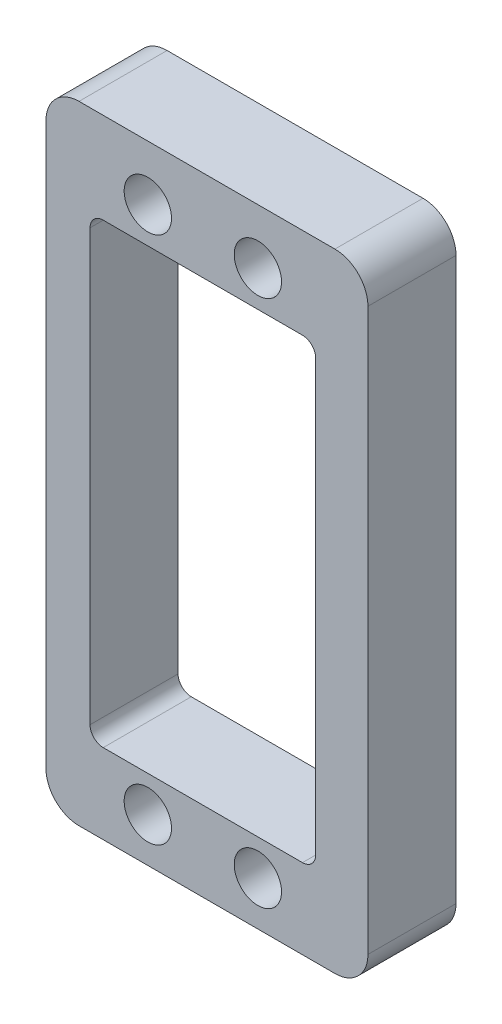
SolidWorks part; units mm, degrees
material "玻纤"
ref_plane "前视基准面" through (0, 0, 0) normal (0, 0, 1) x (1, 0, 0)
ref_plane "上视基准面" through (0, 0, 0) normal (0, 1, 0) x (1, 0, 0)
ref_plane "右视基准面" through (0, 0, 0) normal (1, 0, 0) x (0, 0, -1)
sketch "草图1" plane through (0, 0, 0) normal (0, 0, 1) x (1, 0, 0)
  line L1 (0, 0) -> (100, 0)
  line L2 (0, 0) -> (0, -100)
  line L3 (0, -100) -> (100, -100)
  line L4 (100, 0) -> (100, -100)
  dimension "D1" = 100
  dimension "D2" = 100
extrude "凸台-拉伸1" add sketch "草图1" along normal blind 8
sketch "草图2" plane through (0, 0, 8) normal (0, 0, 1) x (1, 0, 0)
  line L4 (0, 0) -> (0, -100)
  line L5 (0, -100) -> (100, -100)
  line L6 (100, -100) -> (100, 0)
  line L7 (100, 0) -> (0, 0)
  line L8 (0, 0) -> (0, -100)
  line L9 (0, -100) -> (100, -100)
  line L10 (100, -100) -> (100, 0)
  line L11 (100, 0) -> (0, 0)
  circle A0 centre (80, -53) radius 2.15
  circle A1 centre (90, -53) radius 2.15
  circle A2 centre (90, -5) radius 2.15
  circle A3 centre (80, -5) radius 2.15
  dimension "D2" = 4.3
  dimension "D5" = 10
  dimension "D6" = 48
  dimension "D7" = 5
  dimension "D8" = 10
  dimension "D1" = 0
  dimension "D3" = 2
  dimension "D4" = 2
extrude "切除-拉伸1" cut sketch "草图2" against normal through all contours A3 | A2 | A0 | A1
sketch "草图3" plane through (0, 0, 8) normal (0, 0, 1) x (1, 0, 0)
  line L4 (0, 0) -> (0, -100)
  line L5 (0, -100) -> (100, -100)
  line L6 (100, -100) -> (100, 0)
  line L7 (100, 0) -> (0, 0)
  line L8 (0, 0) -> (0, -100)
  line L9 (0, -100) -> (100, -100)
  line L10 (100, -100) -> (100, 0)
  line L11 (100, 0) -> (0, 0)
  circle A0 centre (73, -95) radius 2.15
  circle A1 centre (73, -85) radius 2.15
  circle A2 centre (85, -85) radius 2.15
  circle A3 centre (85, -95) radius 2.15
  dimension "D2" = 4.3
  dimension "D5" = 10
  dimension "D6" = 12
  dimension "D7" = 5
  dimension "D8" = 15
  dimension "D1" = 0
  dimension "D3" = 2
  dimension "D4" = 2
extrude "切除-拉伸2" cut sketch "草图3" against normal through all contours A1 | A2 | A3 | A0
sketch "草图4" plane through (0, 0, 8) normal (0, 0, 1) x (1, 0, 0)
  line L4 (0, 0) -> (0, -100)
  line L5 (0, -100) -> (100, -100)
  line L6 (100, -100) -> (100, 0)
  line L7 (100, 0) -> (0, 0)
  line L8 (0, 0) -> (0, -100)
  line L9 (0, -100) -> (100, -100)
  line L10 (100, -100) -> (100, 0)
  line L11 (100, 0) -> (0, 0)
  circle A0 centre (71.5, -100) radius 9.5
  circle M5 centre (73, -95) radius 2.15
  dimension "D2" = 19
  dimension "D3" = 28.5
  dimension "D1" = 0
extrude "切除-拉伸3" cut sketch "草图4" against normal through all contours L9 A0 M5
sketch "草图5" plane through (0, 0, 8) normal (0, 0, 1) x (1, 0, 0)
  line L0 (85, -1.0404) -> (85, -63.0979) construction
  line L1 (65.9696, -29) -> (93.5663, -29) construction
  line L3 (74.75, -8.25) -> (95.25, -8.25)
  line L4 (74.75, -8.25) -> (74.75, -49.75)
  line L5 (81, -100) -> (100, -100)
  line L6 (100, -100) -> (100, 0)
  line L7 (100, 0) -> (0, 0)
  line L8 (0, 0) -> (0, -100)
  line L9 (0, -100) -> (62, -100)
  line L10 (81, -100) -> (100, -100)
  line L11 (100, -100) -> (100, 0)
  line L12 (100, 0) -> (0, 0)
  line L13 (0, 0) -> (0, -100)
  line L14 (0, -100) -> (62, -100)
  line L15 (74.75, -49.75) -> (95.25, -49.75)
  line L16 (95.25, -8.25) -> (95.25, -49.75)
  circle A0 centre (80, -5) radius 2.15 construction
  arc A1 (81, -100) -> (62, -100) centre (71.5, -100) ccw
  arc A2 (81, -100) -> (62, -100) centre (71.5, -100) ccw
  circle A3 centre (80, -5) radius 2.15
  circle A4 centre (90, -5) radius 2.15 construction
  circle A5 centre (90, -5) radius 2.15
  circle A6 centre (80, -53) radius 2.15 construction
  circle A7 centre (80, -53) radius 2.15
  circle A8 centre (90, -53) radius 2.15 construction
  circle A9 centre (90, -53) radius 2.15
  dimension "D2" = 41.5
  dimension "D3" = 20.5
  dimension "D1" = 0
extrude "切除-拉伸4" cut sketch "草图5" against normal blind 10 contours L4 L3 L16 L15
sketch "草图6" plane through (0, 0, 8) normal (0, 0, 1) x (1, 0, 0)
  line L0 (55, 0) -> (55, -100)
  line L5 (81, -100) -> (100, -100)
  line L6 (100, -100) -> (100, 0)
  line L7 (100, 0) -> (0, 0)
  line L8 (0, 0) -> (0, -100)
  line L9 (0, -100) -> (62, -100)
  line L10 (81, -100) -> (100, -100)
  line L11 (100, -100) -> (100, 0)
  line L12 (100, 0) -> (0, 0)
  line L13 (0, 0) -> (0, -100)
  line L14 (0, -100) -> (62, -100)
  circle A0 centre (73, -85) radius 2.15 construction
  arc A1 (81, -100) -> (62, -100) centre (71.5, -100) ccw
  arc A2 (81, -100) -> (62, -100) centre (71.5, -100) ccw
  circle A3 centre (73, -85) radius 2.15
  dimension "D2" = 45
  dimension "D1" = 0
extrude "切除-拉伸5" cut sketch "草图6" against normal blind 10
fillet "圆角2" radius 1.2 4 edges at (74.75, -8.25, 4) (95.25, -49.75, 4) (74.75, -49.75, 4) (95.25, -8.25, 4)
sketch "草图8" plane through (0, 0, 8) normal (0, 0, 1) x (1, 0, 0)
  line L5 (100, 0) -> (55, 0)
  line L6 (55, 0) -> (55, -100)
  line L7 (55, -100) -> (62, -100)
  line L8 (81, -100) -> (100, -100)
  line L9 (100, -100) -> (100, 0)
  line L10 (100, 0) -> (55, 0)
  line L11 (55, 0) -> (55, -100)
  line L12 (55, -100) -> (62, -100)
  line L13 (81, -100) -> (100, -100)
  line L14 (100, -100) -> (100, 0)
  circle A0 centre (59, -84) radius 1.65
  arc A1 (81, -100) -> (62, -100) centre (71.5, -100) ccw
  arc A2 (81, -100) -> (62, -100) centre (71.5, -100) ccw
  circle A3 centre (73, -85) radius 2.15 construction
  circle A4 centre (73, -85) radius 2.15
  dimension "D2" = 3.3
  dimension "D4" = 14
  dimension "D3" = 1
  dimension "D1" = 0
extrude "切除-拉伸6" cut sketch "草图8" against normal through all contours A0
sketch "草图9" plane through (0, 0, 8) normal (0, 0, 1) x (1, 0, 0)
  line L0 (55, -90.5) -> (71.5, -90.5)
  line L1 (55, -78.5) -> (70.75, -78.5)
  line L2 (70.75, -78.5) -> (70.75, 0)
  line L3 (74.75, -9.45) -> (74.75, -48.55) construction
  line L5 (100, 0) -> (55, 0)
  line L6 (55, 0) -> (55, -100)
  line L7 (55, -100) -> (62, -100)
  line L8 (81, -100) -> (100, -100)
  line L9 (100, -100) -> (100, 0)
  line L10 (100, 0) -> (55, 0)
  line L11 (55, 0) -> (55, -100)
  line L12 (55, -100) -> (62, -100)
  line L13 (81, -100) -> (100, -100)
  line L14 (100, -100) -> (100, 0)
  arc A1 (81, -100) -> (62, -100) centre (71.5, -100) ccw
  arc A2 (81, -100) -> (62, -100) centre (71.5, -100) ccw
  line M26 (100, 0) -> (55, 0)
  line M27 (55, 0) -> (55, -100)
  line M28 (55, -100) -> (62, -100)
  arc M29 (62, -100) -> (81, -100) centre (71.5, -100) cw
  dimension "D2" = 4
  dimension "D3" = 12
  dimension "D1" = 0
extrude "切除-拉伸7" cut sketch "草图9" against normal through all contours L0 M27 M28 M29 | L1 L2 M26 M27
fillet "圆角3" radius 10 1 edges at (70.75, -78.5, 4)
fillet "圆角4" radius 3 6 edges at (81, -100, 4) (100, -100, 4) (100, 0, 4) (70.75, 0, 4) (55, -78.5, 4) (55, -90.5, 4)
sketch "草图10" plane through (0, 0, 8) normal (0, 0, 1) x (1, 0, 0)
  line L0 (70.75, -57) -> (100, -57)
  line L7 (83.6347, -100) -> (97, -100)
  line L8 (100, -97) -> (100, -3)
  line L9 (97, 0) -> (73.75, 0)
  line L10 (70.75, -3) -> (70.75, -68.5)
  line L11 (60.75, -78.5) -> (58, -78.5)
  line L12 (55, -81.5) -> (55, -87.5)
  line L13 (58, -90.5) -> (71.5, -90.5)
  line L14 (83.6347, -100) -> (97, -100)
  line L15 (100, -97) -> (100, -3)
  line L16 (97, 0) -> (73.75, 0)
  line L17 (70.75, -3) -> (70.75, -68.5)
  line L18 (60.75, -78.5) -> (58, -78.5)
  line L19 (55, -81.5) -> (55, -87.5)
  line L20 (58, -90.5) -> (71.5, -90.5)
  arc A8 (80.7223, -97.72) -> (71.5, -90.5) centre (71.5, -100) ccw
  arc A9 (80.7223, -97.72) -> (83.6347, -100) centre (83.6347, -97) ccw
  arc A10 (97, -100) -> (100, -97) centre (97, -97) ccw
  arc A11 (100, -3) -> (97, 0) centre (97, -3) ccw
  arc A12 (73.75, 0) -> (70.75, -3) centre (73.75, -3) ccw
  arc A13 (60.75, -78.5) -> (70.75, -68.5) centre (60.75, -68.5) ccw
  arc A14 (58, -78.5) -> (55, -81.5) centre (58, -81.5) ccw
  arc A15 (55, -87.5) -> (58, -90.5) centre (58, -87.5) ccw
  arc A16 (80.7223, -97.72) -> (71.5, -90.5) centre (71.5, -100) ccw
  arc A17 (80.7223, -97.72) -> (83.6347, -100) centre (83.6347, -97) ccw
  arc A18 (97, -100) -> (100, -97) centre (97, -97) ccw
  arc A19 (100, -3) -> (97, 0) centre (97, -3) ccw
  arc A20 (73.75, 0) -> (70.75, -3) centre (73.75, -3) ccw
  arc A21 (60.75, -78.5) -> (70.75, -68.5) centre (60.75, -68.5) ccw
  arc A22 (58, -78.5) -> (55, -81.5) centre (58, -81.5) ccw
  arc A23 (55, -87.5) -> (58, -90.5) centre (58, -87.5) ccw
  circle M17 centre (59, -84) radius 1.65
  circle M26 centre (85, -95) radius 2.15
  circle M27 centre (85, -85) radius 2.15
  circle M28 centre (73, -85) radius 2.15
  arc M33 (71.5, -90.5) -> (80.7223, -97.72) centre (71.5, -100) cw
  arc M34 (80.7223, -97.72) -> (83.6347, -100) centre (83.6347, -97) ccw
  line M35 (83.6347, -100) -> (97, -100)
  arc M36 (97, -100) -> (100, -97) centre (97, -97) ccw
  line M37 (100, -97) -> (100, -3)
  line M41 (70.75, -3) -> (70.75, -68.5)
  arc M42 (70.75, -68.5) -> (60.75, -78.5) centre (60.75, -68.5) cw
  line M43 (60.75, -78.5) -> (58, -78.5)
  arc M44 (58, -78.5) -> (55, -81.5) centre (58, -81.5) ccw
  line M45 (55, -81.5) -> (55, -87.5)
  arc M46 (55, -87.5) -> (58, -90.5) centre (58, -87.5) ccw
  line M47 (58, -90.5) -> (71.5, -90.5)
  dimension "D2" = 57
  dimension "D1" = 0
extrude "切除-拉伸8" cut sketch "草图10" against normal through all contours L0 M41 M42 M43 M44 M45 M46 M47 M33 M34 M35 M36 M37 M26 M28 M27 M17
fillet "圆角5" radius 3 2 edges at (100, -57, 4) (70.75, -57, 4)
